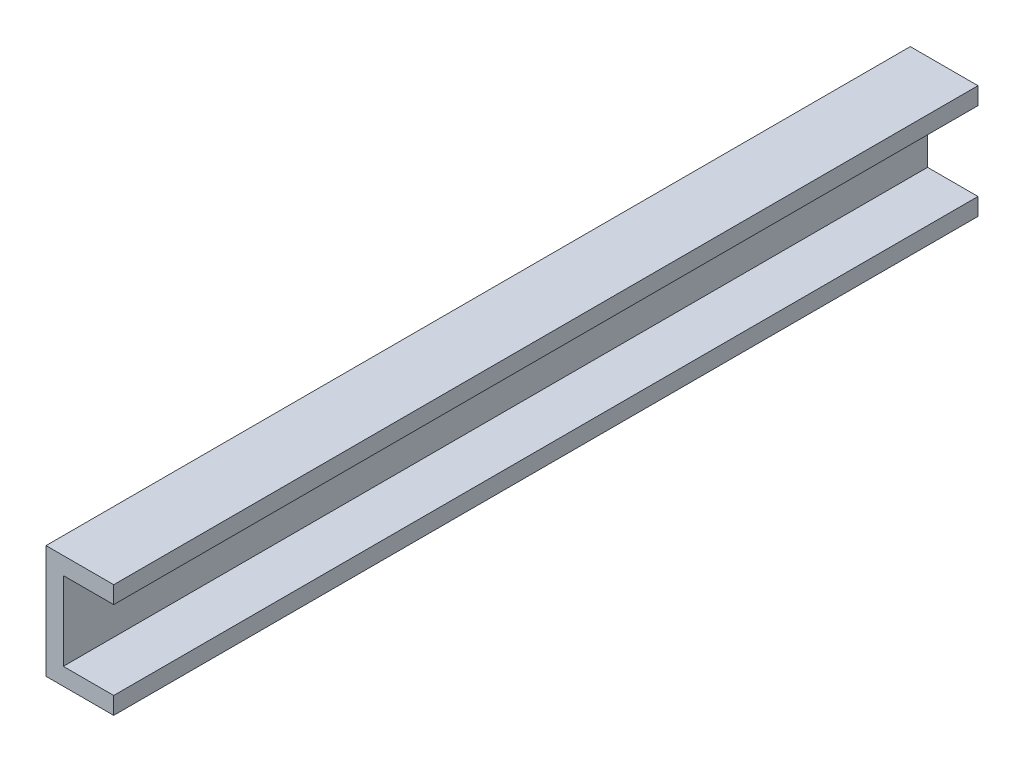
SolidWorks part; units mm, degrees
ref_plane "Front Plane" through (0, 0, 0) normal (0, 0, 1) x (1, 0, 0)
ref_plane "Top Plane" through (0, 0, 0) normal (0, 1, 0) x (1, 0, 0)
ref_plane "Right Plane" through (0, 0, 0) normal (1, 0, 0) x (0, 0, -1)
sketch "Sketch1" plane through (0, 0, 0) normal (0, 0, 1) x (1, 0, 0)
  line L0 (-12.9824, -2.4207) -> (-12.9824, -1.4207)
  line L1 (-16.8998, 4.1293) -> (-12.9824, 4.1293)
  line L2 (-16.8998, 4.1293) -> (-16.8998, -2.4207)
  line L3 (-16.8998, -2.4207) -> (-12.9824, -2.4207)
  line L5 (-12.9824, -1.4207) -> (-15.8998, -1.4207)
  line L6 (-15.8998, -1.4207) -> (-15.8998, 3.1293)
  line L7 (-15.8998, 3.1293) -> (-12.9824, 3.1293)
  line L8 (-12.9824, 3.1293) -> (-12.9824, 4.1293)
  point P4 (-12.958, 9.2205)
  dimension "D1" = 1
  dimension "D2" = 1
  dimension "D3" = 1
  dimension "D4" = 6.55
extrude "Boss-Extrude1" add sketch "Sketch1" along normal blind 50
